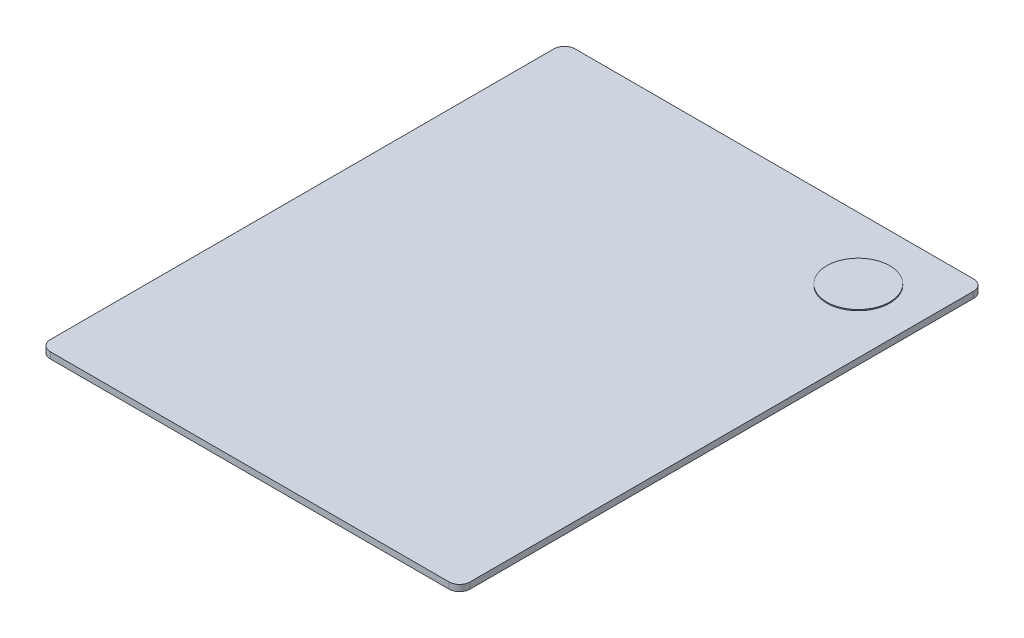
SolidWorks part; units mm, degrees
ref_plane "Front" through (0, 0, 0) normal (0, 0, 1) x (1, 0, 0)
ref_plane "Top" through (0, 0, 0) normal (0, 1, 0) x (1, 0, 0)
ref_plane "Right" through (0, 0, 0) normal (1, 0, 0) x (0, 0, -1)
sketch "Sketch1" plane through (0, 0, 0) normal (0, 1, 0) x (1, 0, 0)
  line L1 (100, 125) -> (-100, 125)
  line L2 (100, 125) -> (100, -125)
  line L3 (100, -125) -> (-100, -125)
  line L4 (-100, 125) -> (-100, -125)
  line L5 (100, 125) -> (-100, -125) construction
  line L6 (100, -125) -> (-100, 125) construction
  point P0 (0, 0)
  dimension "D1" = 200
  dimension "D2" = 250
extrude "Boss-Extrude1" add sketch "Sketch1" along normal blind 3
sketch "Sketch2" plane through (0, 3, 0) normal (0, 1, 0) x (1, 0, 0)
  line L0 (100, -125) -> (100, 125) construction
  line L1 (100, 125) -> (-100, 125) construction
  circle A0 centre (70, 95) radius 15
  dimension "D1" = 30
  dimension "D3" = 30
  dimension "D2" = 30
extrude "Boss-Extrude6" add sketch "Sketch2" along normal blind 0.5 separate body
fillet "Fillet1" radius 5 4 edges at (-100, 1.5, -125) (-100, 1.5, 125) (100, 1.5, 125) (100, 1.5, -125)
